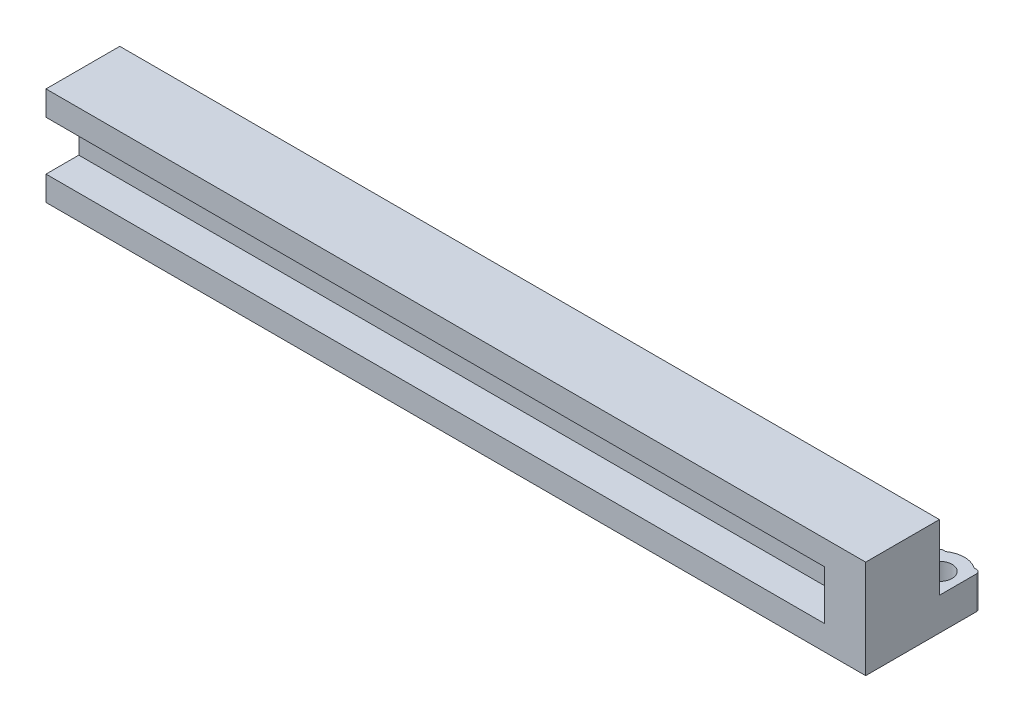
SolidWorks part; units mm, degrees
ref_plane "Plan de face" through (0, 0, 0) normal (0, 0, 1) x (1, 0, 0)
ref_plane "Plan de dessus" through (0, 0, 0) normal (0, 1, 0) x (1, 0, 0)
ref_plane "Plan de droite" through (0, 0, 0) normal (1, 0, 0) x (0, 0, -1)
sketch "Esquisse1" plane through (0, 0, 0) normal (0, 0, 1) x (1, 0, 0)
  line L1 (-50, 6) -> (50, 6)
  line L2 (-50, 6) -> (-50, -6)
  line L3 (-50, -6) -> (50, -6)
  line L4 (50, 6) -> (50, -6)
  line L5 (-50, 6) -> (50, -6) construction
  line L6 (-50, -6) -> (50, 6) construction
  point P0 (0, 0)
  dimension "D1" = 12
  dimension "D2" = 100
extrude "Boss.-Extru.1" add sketch "Esquisse1" along normal blind 5
sketch "Esquisse2" plane through (0, 0, 5) normal (0, 0, 1) x (1, 0, 0)
  line L0 (-50, 3) -> (45, 3)
  line L1 (-50, -3) -> (45, -3)
  line L2 (45, 3) -> (45, -3)
  line L3 (-50, -3) -> (-50, -6)
  line L4 (50, -6) -> (50, 6)
  line L5 (50, 6) -> (-50, 6)
  line L6 (-50, 6) -> (-50, -6)
  line L7 (-50, -6) -> (50, -6)
  line L8 (50, -6) -> (50, 6)
  line L9 (50, 6) -> (-50, 6)
  line L10 (-50, 6) -> (-50, 3)
  line L11 (-50, -6) -> (50, -6)
  dimension "D2" = 3
  dimension "D3" = 3
  dimension "D4" = 5
  dimension "D1" = 0
extrude "Boss.-Extru.2" add sketch "Esquisse2" along normal blind 4
sketch "Esquisse3" plane through (0, -6, 0) normal (0, -1, 0) x (1, 0, 0)
  line L0 (-45.7117, -5) -> (-45.5, -5)
  line L1 (-50, 0) -> (-45, 0)
  line L2 (-50, 0) -> (-50, -4.5)
  line L3 (-49.5, -5) -> (-49.2883, -5)
  line L4 (-45, 0) -> (-45, -4.5)
  line L5 (-47.5, -6.9236) -> (-47.5, 0.5552) construction
  line L6 (0, 20.1164) -> (0, -15.1947) construction
  line L7 (49.5, -5) -> (49.2883, -5)
  line L8 (50, 0) -> (50, -4.5)
  line L9 (50, 0) -> (45, 0)
  line L10 (45, 0) -> (45, -4.5)
  line L11 (45.7117, -5) -> (45.5, -5)
  line L12 (-2.5, 0) -> (-2.5, -4.5)
  line L13 (2.5, 0) -> (2.5, -4.5)
  line L14 (-2, -5) -> (-1.7883, -5)
  line L15 (1.7883, -5) -> (2, -5)
  line L16 (-2.5, 0) -> (2.5, 0)
  circle A0 centre (-47.5, -2.5456) radius 1.5
  arc A1 (-49.1747, -5.0347) -> (-45.8253, -5.0347) centre (-47.5, -2.5456) ccw
  arc A2 (-49.1747, -5.0347) -> (-49.2883, -5) centre (-49.2883, -5.2035) ccw
  arc A3 (-45.8253, -5.0347) -> (-45.7117, -5) centre (-45.7117, -5.2035) cw
  arc A4 (-45.5, -5) -> (-45, -4.5) centre (-45.5, -4.5) ccw
  arc A5 (-50, -4.5) -> (-49.5, -5) centre (-49.5, -4.5) ccw
  circle A6 centre (47.5, -2.5456) radius 1.5
  arc A7 (49.1747, -5.0347) -> (49.2883, -5) centre (49.2883, -5.2035) cw
  arc A8 (50, -4.5) -> (49.5, -5) centre (49.5, -4.5) cw
  arc A9 (45.5, -5) -> (45, -4.5) centre (45.5, -4.5) cw
  arc A10 (45.8253, -5.0347) -> (45.7117, -5) centre (45.7117, -5.2035) ccw
  arc A11 (49.1747, -5.0347) -> (45.8253, -5.0347) centre (47.5, -2.5456) cw
  circle A12 centre (0, -2.5456) radius 1.5
  arc A13 (-1.6747, -5.0347) -> (-1.7883, -5) centre (-1.7883, -5.2035) ccw
  arc A14 (1.6747, -5.0347) -> (1.7883, -5) centre (1.7883, -5.2035) cw
  arc A15 (-1.6747, -5.0347) -> (1.6747, -5.0347) centre (0, -2.5456) ccw
  arc A16 (-2.5, -4.5) -> (-2, -5) centre (-2, -4.5) ccw
  arc A17 (2, -5) -> (2.5, -4.5) centre (2, -4.5) ccw
  point P17 (-45, -5)
  point P20 (-50, -5)
  dimension "D3" = 3
  dimension "D4" = 6
  dimension "D5" = 0.5
  dimension "D1" = 5
  dimension "D2" = 5
extrude "Boss.-Extru.3" add sketch "Esquisse3" against normal blind 4
